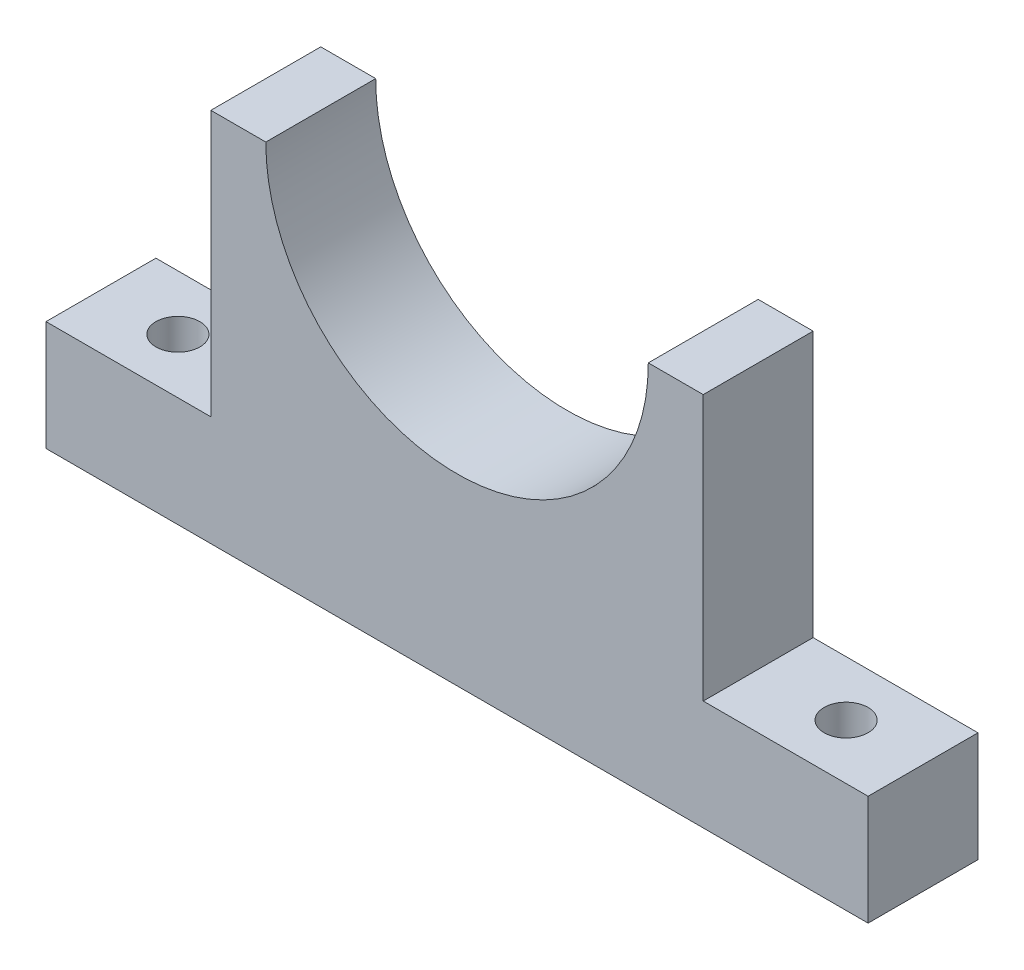
SolidWorks part; units mm, degrees
ref_plane "Plan de face" through (0, 0, 0) normal (0, 0, 1) x (1, 0, 0)
ref_plane "Plan de dessus" through (0, 0, 0) normal (0, 1, 0) x (1, 0, 0)
ref_plane "Plan de droite" through (0, 0, 0) normal (1, 0, 0) x (0, 0, -1)
sketch "Esquisse1" plane through (0, 0, 0) normal (0, 0, 1) x (1, 0, 0)
  line L0 (-22.3999, 17.075) -> (-17.3999, 17.075)
  line L1 (-22.3999, -17.075) -> (22.3999, -17.075)
  line L2 (-22.3999, -17.075) -> (-22.3999, 17.075)
  line L4 (22.3999, -17.075) -> (22.3999, 17.075)
  line L5 (-22.3999, -17.075) -> (22.3999, 17.075) construction
  line L6 (-22.3999, 17.075) -> (22.3999, -17.075) construction
  line L7 (17.3999, 17.075) -> (22.3999, 17.075)
  arc A1 (17.3999, 17.075) -> (-17.3999, 17.075) centre (0, 17.025) cw
  point P0 (0, 0)
  dimension "D2" = 5
  dimension "D1" = 17.4
  dimension "D3" = 34.15
  dimension "D4" = 5
  dimension "D5" = 34.1
  dimension "D6" = 34.15
extrude "Boss.-Extru.1" add sketch "Esquisse1" along normal blind 10
sketch "Esquisse2" plane through (-22.3999, 0, 0) normal (-1, 0, 0) x (0, 0, 1)
  line L0 (10, 17.075) -> (10, -17.075) construction
  line L1 (0, -17.075) -> (10, -17.075)
  line L2 (0, -17.075) -> (0, -7.075)
  line L3 (0, -7.075) -> (10, -7.075)
  line L4 (10, -17.075) -> (10, -7.075)
  dimension "D1" = 10
extrude "Boss.-Extru.2" add sketch "Esquisse2" along normal blind 15
sketch "Esquisse3" plane through (22.3999, 0, 0) normal (1, 0, 0) x (0, 0, -1)
  line L0 (0, -17.075) -> (0, 17.075) construction
  line L1 (-10, -17.075) -> (0, -17.075)
  line L2 (-10, -17.075) -> (-10, -7.075)
  line L3 (-10, -7.075) -> (0, -7.075)
  line L4 (0, -17.075) -> (0, -7.075)
  dimension "D1" = 10
extrude "Boss.-Extru.3" add sketch "Esquisse3" along normal blind 15
sketch "Esquisse4" plane through (0, -7.075, 0) normal (0, 1, 0) x (1, 0, 0)
  line L1 (-37.3999, -10) -> (-37.3999, 0) construction
  line L2 (-37.3999, 0) -> (-22.3999, 0) construction
  line L3 (0, 0) -> (0, -10) construction
  line L4 (-17.4, -10) -> (17.4, -10) construction
  circle A0 centre (-30.3999, -5) radius 2
  circle A1 centre (30.3999, -5) radius 2
  dimension "D1" = 4
  dimension "D2" = 7
  dimension "D3" = 5
extrude "Enlèv. mat.-Extru.1" cut sketch "Esquisse4" against normal blind 20
